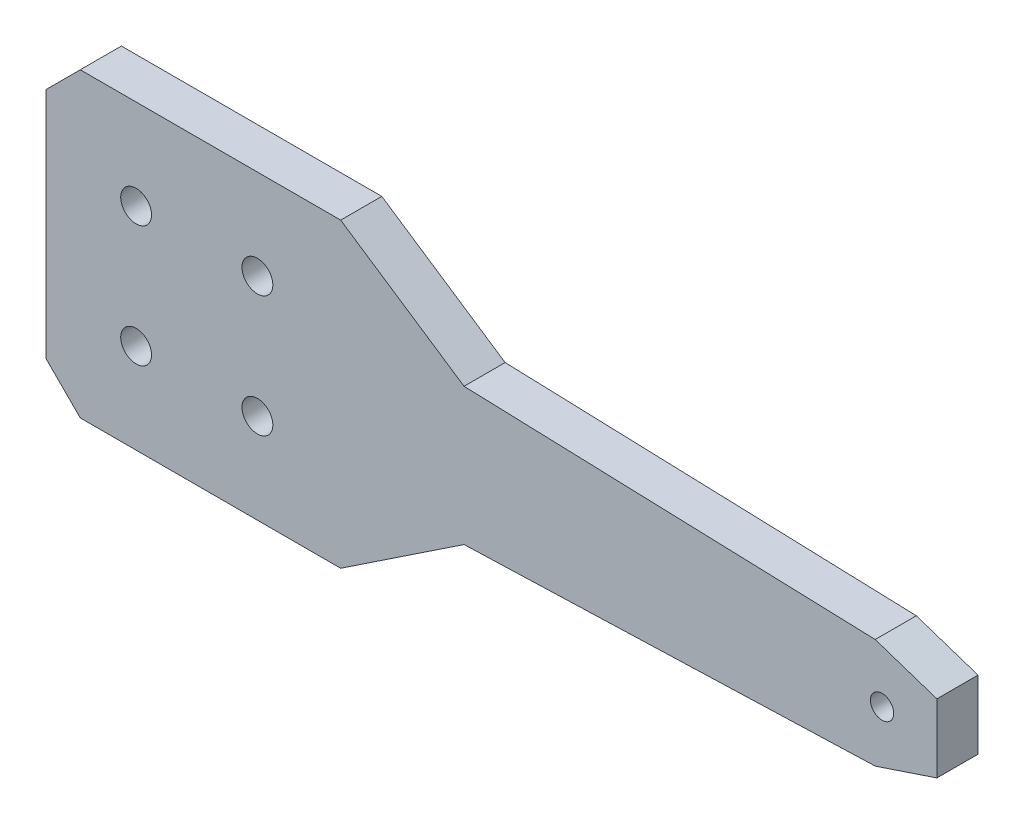
SolidWorks part; units mm, degrees
ref_plane "前视基准面" through (0, 0, 0) normal (0, 0, 1) x (1, 0, 0)
ref_plane "上视基准面" through (0, 0, 0) normal (0, 1, 0) x (1, 0, 0)
ref_plane "右视基准面" through (0, 0, 0) normal (1, 0, 0) x (0, 0, -1)
other "Configuration Table"
sketch "草图1" plane through (0, 0, 0) normal (0, 0, 1) x (1, 0, 0)
  line L0 (-22, -17) -> (-17, -22)
  line L1 (-17, -22) -> (21, -22)
  line L2 (21, -22) -> (39, -10)
  line L3 (39, -10) -> (99, -8)
  line L4 (99, -8) -> (108, -5)
  line L5 (108, -5) -> (108, 5)
  line L6 (108, 5) -> (99, 8)
  line L7 (99, 8) -> (39, 10)
  line L8 (39, 10) -> (21, 22)
  line L9 (21, 22) -> (-17, 22)
  line L10 (-17, 22) -> (-22, 17)
  line L11 (-22, 17) -> (-22, -17)
  circle A0 centre (-8.85, -8.85) radius 2.25
  circle A1 centre (-8.85, 8.85) radius 2.25
  circle A2 centre (8.85, -8.85) radius 2.25
  circle A3 centre (8.85, 8.85) radius 2.25
  circle A4 centre (100, 0) radius 1.7
extrude "板体与通孔" add sketch "草图1" along normal blind 6 from offset 0
